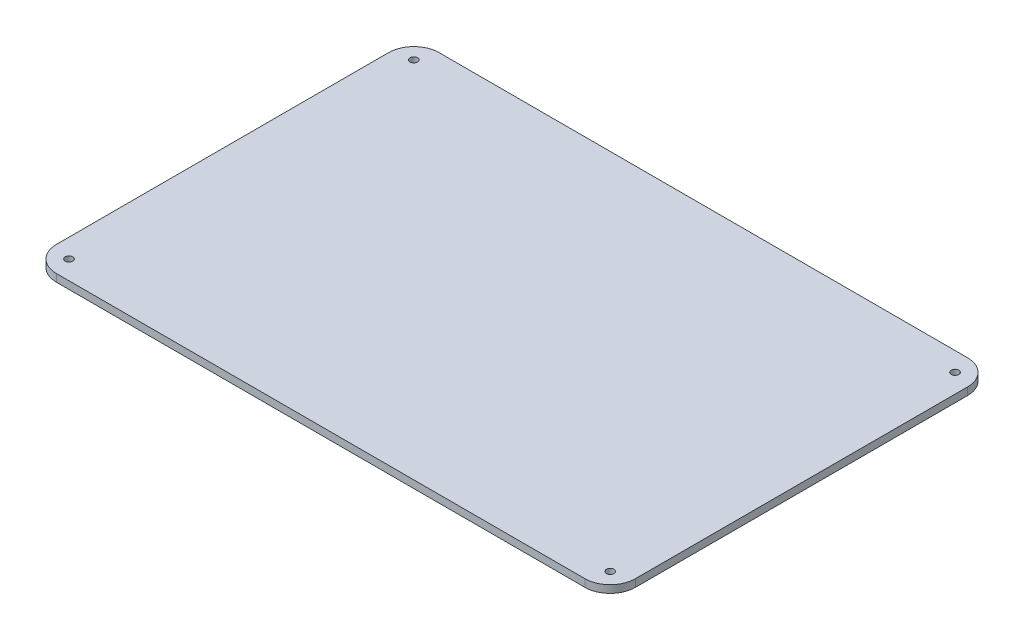
SolidWorks part; units mm, degrees
ref_plane "Спереди" through (0, 0, 0) normal (0, 0, 1) x (1, 0, 0)
ref_plane "Сверху" through (0, 0, 0) normal (0, 1, 0) x (1, 0, 0)
ref_plane "Справа" through (0, 0, 0) normal (1, 0, 0) x (0, 0, -1)
sketch "Эскиз1" plane through (0, 0, 0) normal (0, 1, 0) x (1, 0, 0)
  line L1 (-153.9032, 45.5) -> (76.0968, 45.5)
  line L2 (-153.9032, 45.5) -> (-153.9032, -106.5)
  line L3 (-153.9032, -106.5) -> (76.0968, -106.5)
  line L4 (76.0968, 45.5) -> (76.0968, -106.5)
  dimension "D1" = 230
  dimension "D2" = 152
extrude "Бобышка-Вытянуть1" add sketch "Эскиз1" along normal blind 3
sketch "Эскиз2" plane through (0, 3, 0) normal (0, 1, 0) x (1, 0, 0)
  line L0 (76.0968, 45.5) -> (-153.9032, 45.5) construction
  line L1 (-153.9032, 45.5) -> (-153.9032, -106.5) construction
  line L2 (76.0968, -106.5) -> (76.0968, 45.5) construction
  line L3 (-153.9032, -106.5) -> (76.0968, -106.5) construction
  circle A0 centre (-146.4032, 38) radius 1.5
  circle A1 centre (68.5968, 38) radius 1.5
  circle A2 centre (68.5968, -99) radius 1.5
  circle A3 centre (-146.4032, -99) radius 1.5
  dimension "D1" = 3
  dimension "D2" = 3
  dimension "D3" = 3
  dimension "D4" = 3
  dimension "D5" = 7.5
  dimension "D6" = 7.5
  dimension "D7" = 7.5
  dimension "D8" = 7.5
  dimension "D9" = 7.5
  dimension "D10" = 7.5
  dimension "D11" = 7.5
  dimension "D12" = 7.5
extrude "Вырез-Вытянуть1" cut sketch "Эскиз2" against normal blind 3
fillet "Скругление1" radius 10 4 edges at (76.0968, 1.5, 106.5) (-153.9032, 1.5, 106.5) (76.0968, 1.5, -45.5) (-153.9032, 1.5, -45.5)
